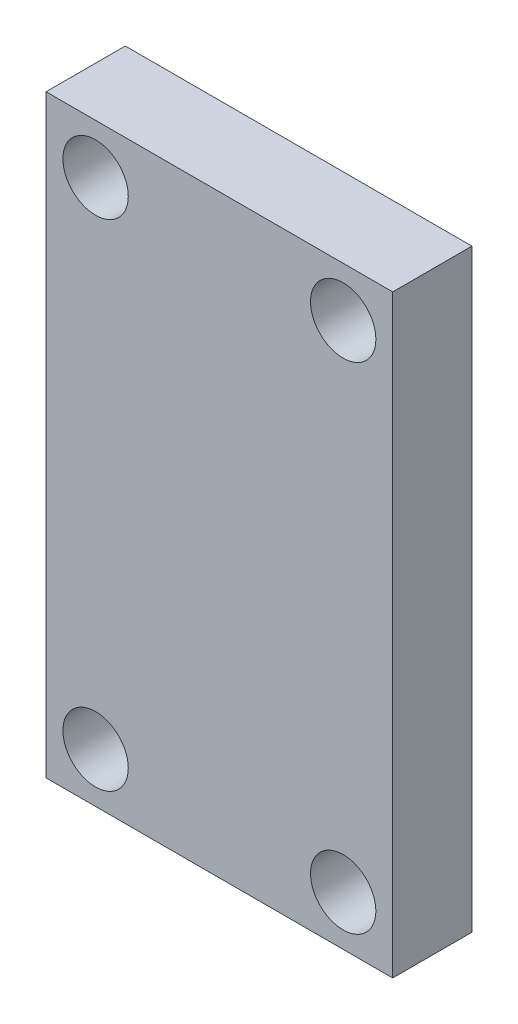
SolidWorks part; units mm, degrees
ref_plane "Front Plane" through (0, 0, 0) normal (0, 0, 1) x (1, 0, 0)
ref_plane "Top Plane" through (0, 0, 0) normal (0, 1, 0) x (1, 0, 0)
ref_plane "Right Plane" through (0, 0, 0) normal (1, 0, 0) x (0, 0, -1)
sketch "Sketch1" plane through (0, 0, 0) normal (0, 0, 1) x (1, 0, 0)
  line L1 (-17.5, 30) -> (17.5, 30)
  line L2 (-17.5, 30) -> (-17.5, -30)
  line L3 (-17.5, -30) -> (17.5, -30)
  line L4 (17.5, 30) -> (17.5, -30)
  line L5 (0, -30) -> (0, 30) construction
  line L6 (-17.5, 0) -> (17.5, 0) construction
  point P0 (0, 0)
  dimension "D1" = 60
  dimension "D2" = 35
extrude "Boss-Extrude1" add sketch "Sketch1" along normal mid plane 8
hole_wizard "M6 Clearance Hole1" positions "Sketch4" profile "Sketch3" hole size "M6" standard "ISO"
sketch "Sketch4" plane through (0, 0, 4) normal (0, 0, 1) x (1, 0, 0)
  line L0 (-17.5, 30) -> (-17.5, -30) construction
  line L1 (-17.5, 30) -> (17.5, 30) construction
  point P0 (-12.5, 25)
  dimension "D1" = 5
  dimension "D2" = 5
sketch "Sketch3" plane through (-12.5, 25, 4) normal (1, 0, 0) x (0, -1, 0)
  line L0 (0, 0) -> (0, 9.9828)
  line L1 (0, 9.9828) -> (3.3, 8)
  line L2 (3.3, 8) -> (3.3, 0)
  line L5 (3.3, 0) -> (0, 0)
  line L10 (0, 9.9828) -> (-3.3, 8) construction
  line L11 (0, -6.35) -> (0, 107.95) construction
  dimension "Hole Dia." = 6.6
  dimension "Hole Depth" = 8
  dimension "Drill Angle" = 118
mirror "Mirror1" about plane through (0, 0, 0) normal (1, 0, 0) of "M6 Clearance Hole1"
mirror "Mirror2" about plane through (0, 0, 0) normal (0, 1, 0) of "Mirror1", "M6 Clearance Hole1"
